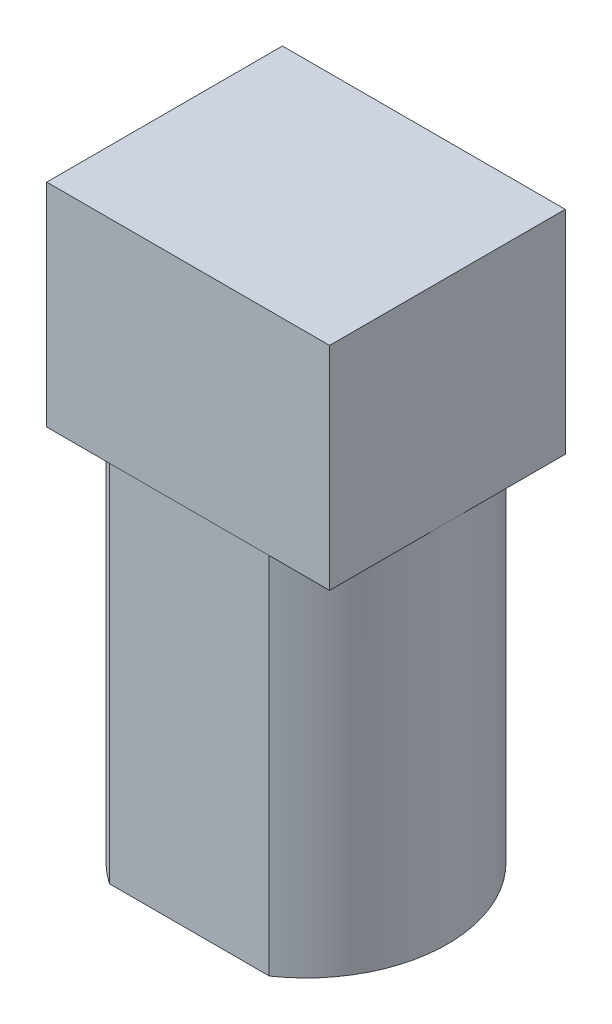
SolidWorks part; units mm, degrees
ref_plane "Front Plane" through (0, 0, 0) normal (0, 0, 1) x (1, 0, 0)
ref_plane "Top Plane" through (0, 0, 0) normal (0, 1, 0) x (1, 0, 0)
ref_plane "Right Plane" through (0, 0, 0) normal (1, 0, 0) x (0, 0, -1)
sketch "Sketch1" plane through (0, 0, 0) normal (0, 1, 0) x (1, 0, 0)
  line L0 (-3.3908, 4.95) -> (3.3908, 4.95)
  line L1 (-3.3908, -4.95) -> (3.3908, -4.95)
  arc A0 (-3.3908, 4.95) -> (-3.3908, -4.95) centre (0, 0) ccw
  arc A1 (3.3908, -4.95) -> (3.3908, 4.95) centre (0, 0) ccw
  dimension "D1" = 12
  dimension "D2" = 9.9
  dimension "D3" = 4.95
extrude "Boss-Extrude1" add sketch "Sketch1" along normal blind 15.5
sketch "Sketch2" plane through (0, 15.5, 0) normal (0, 1, 0) x (1, 0, 0)
  line L1 (-6, -5) -> (6, -5)
  line L2 (-6, -5) -> (-6, 5)
  line L3 (-6, 5) -> (6, 5)
  line L4 (6, -5) -> (6, 5)
  dimension "D1" = 6
  dimension "D2" = 6
  dimension "D3" = 5
  dimension "D4" = 5
extrude "Boss-Extrude2" add sketch "Sketch2" along normal blind 9
